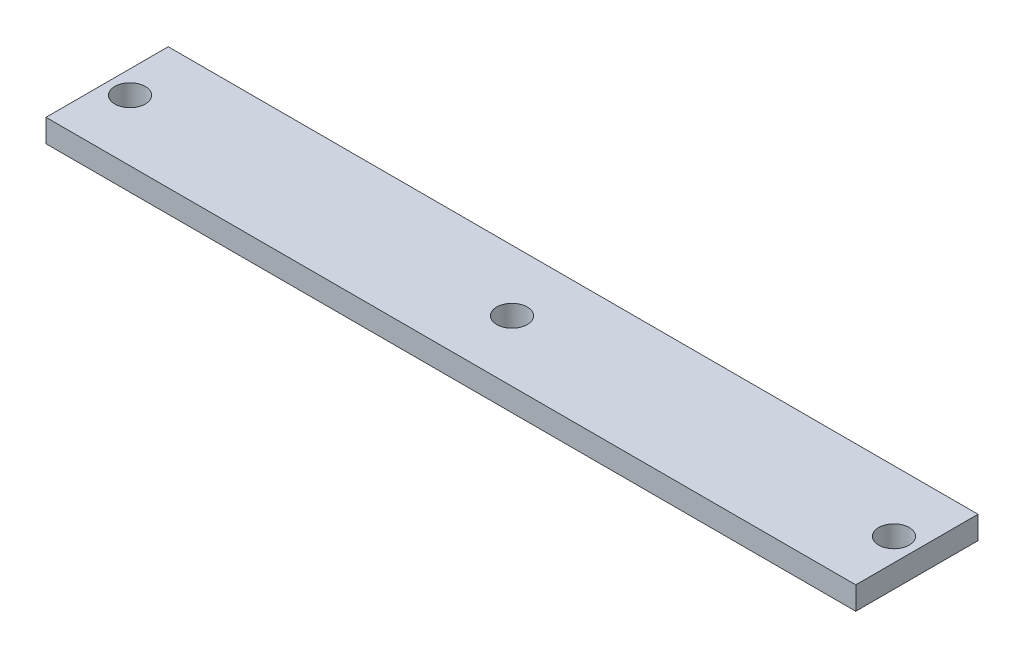
SolidWorks part; units mm, degrees
ref_plane "정면" through (0, 0, 0) normal (0, 0, 1) x (1, 0, 0)
ref_plane "윗면" through (0, 0, 0) normal (0, 1, 0) x (1, 0, 0)
ref_plane "우측면" through (0, 0, 0) normal (1, 0, 0) x (0, 0, -1)
sketch "스케치1" plane through (0, 0, 0) normal (0, 1, 0) x (1, 0, 0)
  line L1 (-53, -8) -> (53, -8)
  line L2 (-53, -8) -> (-53, 8)
  line L3 (-53, 8) -> (53, 8)
  line L4 (53, -8) -> (53, 8)
  line L5 (-53, -8) -> (53, 8) construction
  line L6 (-53, 8) -> (53, -8) construction
  point P0 (0, 0)
  dimension "D1" = 16
  dimension "D2" = 106
extrude "보스-돌출1" add sketch "스케치1" along normal mid plane 3
sketch "스케치2" plane through (0, 1.5, 4.5) normal (0, -1, 0) x (-1, 0, 0)
  line L1 (-53, 4.5) -> (53, 4.5) construction
  line L3 (53, 4.5) -> (-53, 4.5) construction
  line L4 (53, 12.5) -> (53, -3.5) construction
  line L5 (-53, -3.5) -> (-53, 12.5) construction
  circle A0 centre (0, 4.5) radius 2
  circle A1 centre (50, 4.5) radius 2
  circle A2 centre (-50, 4.5) radius 2
  dimension "D3" = 4
  dimension "D4" = 4
  dimension "D5" = 4
  dimension "D1" = 3
  dimension "D2" = 3
extrude "컷-돌출1" cut sketch "스케치2" along normal through all contours A1 | A0 | A2
